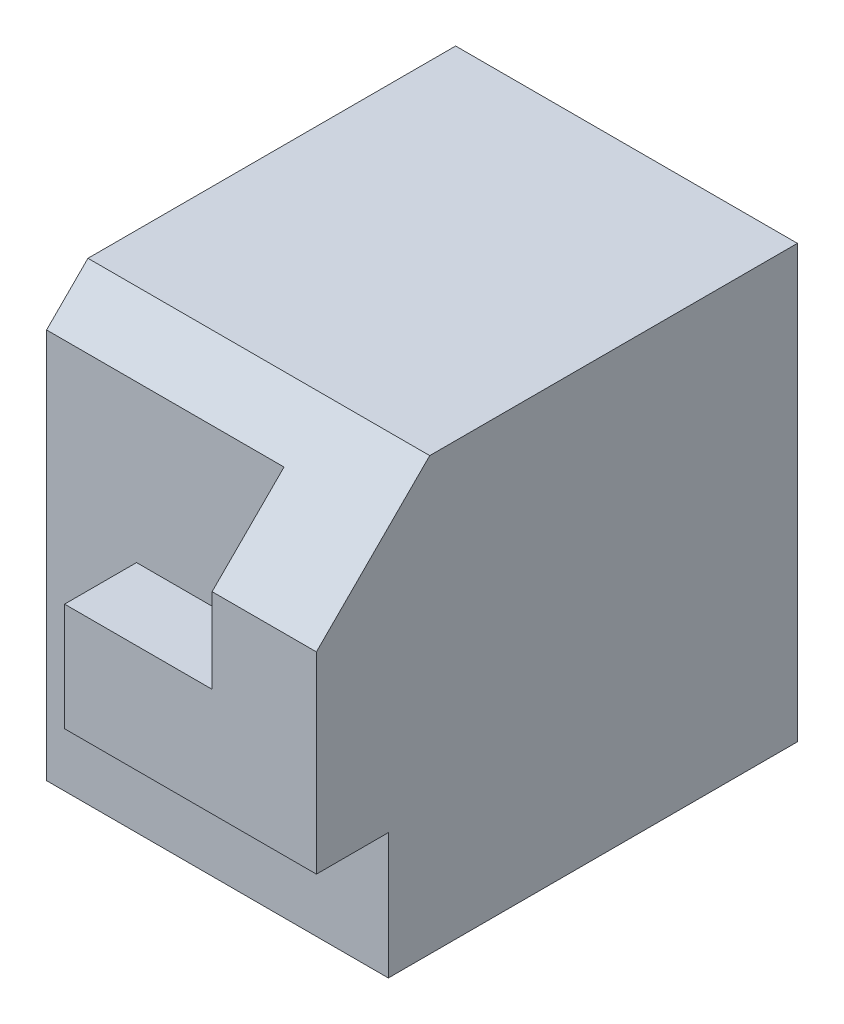
SolidWorks part; units mm, degrees
ref_plane "正面" through (0, 0, 0) normal (0, 0, 1) x (1, 0, 0)
ref_plane "平面" through (0, 0, 0) normal (0, 1, 0) x (1, 0, 0)
ref_plane "右側面" through (0, 0, 0) normal (1, 0, 0) x (0, 0, -1)
sketch "ｽｹｯﾁ1" plane through (0, 0, 0) normal (0, 0, 1) x (1, 0, 0)
  line L1 (-37.3734, 2380.0917) -> (1862.6266, 2380.0917)
  line L2 (-37.3734, 2380.0917) -> (-37.3734, -19.9083)
  line L3 (-37.3734, -19.9083) -> (1862.6266, -19.9083)
  line L4 (1862.6266, 2380.0917) -> (1862.6266, -19.9083)
  dimension "D1" = 1900
  dimension "D2" = 2400
extrude "ﾎﾞｽ - 押し出し1" add sketch "ｽｹｯﾁ1" along normal blind 2674
sketch "ｽｹｯﾁ2" plane through (1862.6266, 0, 0) normal (1, 0, 0) x (0, 0, -1)
  line L0 (-2674, 2380.0917) -> (-2674, 1750.0917)
  line L1 (-2674, -19.9083) -> (-2674, 2380.0917) construction
  line L2 (-2674, 1750.0917) -> (-2044, 2380.0917)
  line L3 (-2674, 2380.0917) -> (0, 2380.0917) construction
  line L4 (-2044, 2380.0917) -> (-2674, 2380.0917)
  dimension "D1" = 135
  dimension "D2" = 630
extrude "ｶｯﾄ - 押し出し1" cut sketch "ｽｹｯﾁ2" against normal through all
sketch "ｽｹｯﾁ3" plane through (0, 0, 2674) normal (0, 0, 1) x (1, 0, 0)
  line L0 (462.6266, 1280.0917) -> (1282.6266, 1280.0917)
  line L2 (1282.6266, 1280.0917) -> (1282.6266, 2380.0917)
  line L3 (-37.3734, 2380.0917) -> (1862.6266, 2380.0917) construction
  line L5 (1282.6266, 2380.0917) -> (-37.3734, 2380.0917)
  line L6 (-37.3734, 2380.0917) -> (-37.3734, -19.9083)
  line L8 (-37.3734, -19.9083) -> (462.6266, -19.9083)
  line L9 (-37.3734, -19.9083) -> (1862.6266, -19.9083) construction
  line L10 (462.6266, 680.0917) -> (462.6266, 1280.0917)
  line L11 (1862.6266, -19.9083) -> (1862.6266, 1750.0917) construction
  line L12 (462.6266, -19.9083) -> (1862.6266, -19.9083)
  line L14 (462.6266, 680.0917) -> (1862.6266, 680.0917)
  line L15 (1862.6266, -19.9083) -> (1862.6266, 680.0917)
  dimension "D1" = 500
  dimension "D2" = 1300
  dimension "D3" = 820
  dimension "D4" = 1320
  dimension "D5" = 600
extrude "ｶｯﾄ - 押し出し2" cut sketch "ｽｹｯﾁ3" against normal blind 400
